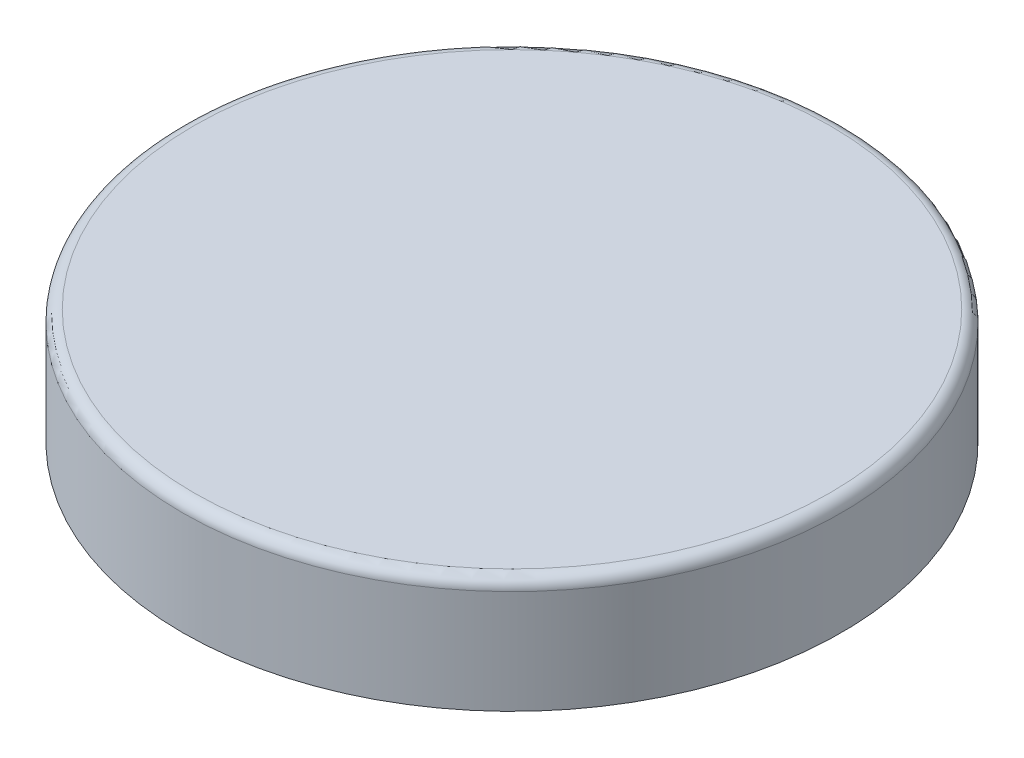
SolidWorks part; units mm, degrees
ref_plane "Plan de face" through (0, 0, 0) normal (0, 0, 1) x (1, 0, 0)
ref_plane "Plan de dessus" through (0, 0, 0) normal (0, 1, 0) x (1, 0, 0)
ref_plane "Plan de droite" through (0, 0, 0) normal (1, 0, 0) x (0, 0, -1)
sketch "Esquisse1" plane through (0, 0, 0) normal (0, 1, 0) x (1, 0, 0)
  circle A0 centre (0, 0) radius 14.3
  dimension "D1" = 28.6
extrude "Boss.-Extru.1" add sketch "Esquisse1" along normal blind 5
shell "Coque1" thickness 0.5
ref_plane "Plan1" through (0, 0, 14.25) normal (0, 0, 1) x (1, 0, 0)
sketch "Esquisse2" plane through (0, 0, 14.25) normal (0, 0, 1) x (1, 0, 0)
  line L0 (-1.1909, -0.0057) -> (1.3091, 4.3244) construction
  line L1 (-1.1909, -0.0057) -> (-2.49, 0.7443) construction
  line L2 (-2.49, 0.7443) -> (0.01, 5.0744) construction
  line L3 (1.3091, 4.3244) -> (0.01, 5.0744) construction
  spline S0 degree 3 poles (0.2837, 4.2254) (0.8364, 4.6889) (0.0495, 4.8518) (-0.4831, 4.3545) (-0.7059, 3.7205) (-0.8357, 3.2029) (-1.0692, 2.1849) (-2.3229, -0.6625) (-1.0523, 1.4539) (-0.6157, 2.262) (-0.2665, 3.0727) (-0.0211, 3.795) (0.2837, 4.2254) (0.8364, 4.6889) (0.0495, 4.8518) knots -0.181222 -0.102778 -0.050322 0 0.019678 0.137076 0.173086 0.216071 0.287021 0.51713 0.646238 0.741155 0.818778 0.897222 0.949678 1 1.019678 1.137076 1.173086 only from (0.6595, 4.6994) to (0.6595, 4.6994)
  dimension "D1" = 5
  dimension "D2" = 1.5
fillet "Congé1" radius 0.5 1 edges at (0, 5, 14.3)
